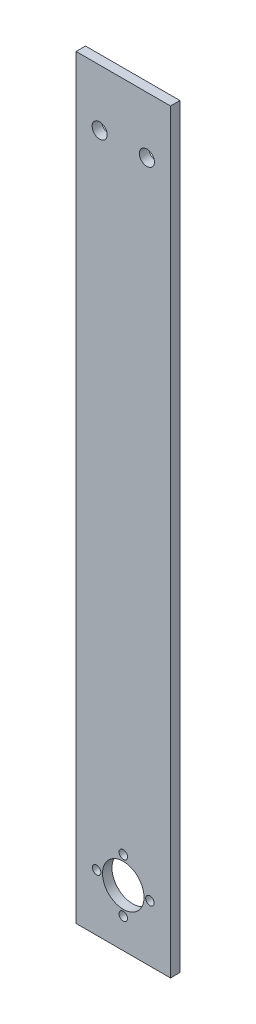
SolidWorks part; units mm, degrees
material "6061 Alloy"
ref_plane "Front Plane" through (0, 0, 0) normal (0, 0, 1) x (1, 0, 0)
ref_plane "Top Plane" through (0, 0, 0) normal (0, 1, 0) x (1, 0, 0)
ref_plane "Right Plane" through (0, 0, 0) normal (1, 0, 0) x (0, 0, -1)
sketch "Sketch1" plane through (0, 0, 0) normal (0, 0, 1) x (1, 0, 0)
  line L1 (-13.5264, 61.7307) -> (36.4736, 61.7307)
  line L2 (-13.5264, 61.7307) -> (-13.5264, -338.2693)
  line L3 (-13.5264, -338.2693) -> (36.4736, -338.2693)
  line L4 (36.4736, 61.7307) -> (36.4736, -338.2693)
  circle A0 centre (-1.0264, 31.7307) radius 4
  circle A1 centre (23.9736, 31.7307) radius 4
  dimension "D3" = 8
  dimension "D4" = 8
  dimension "D6" = 12.5
  dimension "D8" = 30
  dimension "D1" = 50
  dimension "D2" = 400
  dimension "D5" = 12.5
  dimension "D7" = 30
extrude "Boss-Extrude1" add sketch "Sketch1" along normal blind 5
sketch "Sketch2" plane through (0, 0, 0) normal (0, 0, -1) x (-1, 0, 0)
  line L2 (-36.4736, -338.2693) -> (-36.4736, 61.7307) construction
  line L3 (13.5264, -338.2693) -> (-36.4736, -338.2693) construction
  line L4 (13.5264, 61.7307) -> (13.5264, -338.2693) construction
  circle A2 centre (-11.4736, -322.3943) radius 2.25
  circle A3 centre (2.6514, -308.2693) radius 2.25
  circle A4 centre (-11.4736, -294.1443) radius 2.25
  circle A5 centre (-25.5986, -308.2693) radius 2.25
  circle A6 centre (-11.4736, -308.2693) radius 11
  dimension "D1" = 22
  dimension "D2" = 28.25
  dimension "D3" = 28.25
  dimension "D5" = 25
  dimension "D6" = 30
  dimension "D7" = 14.125
  dimension "D8" = 25
  dimension "D9" = 4.5
  dimension "D10" = 4.5
  dimension "D11" = 4.5
  dimension "D12" = 4.5
  dimension "D4" = 14.125
extrude "Cut-Extrude1" cut sketch "Sketch2" against normal blind 10
